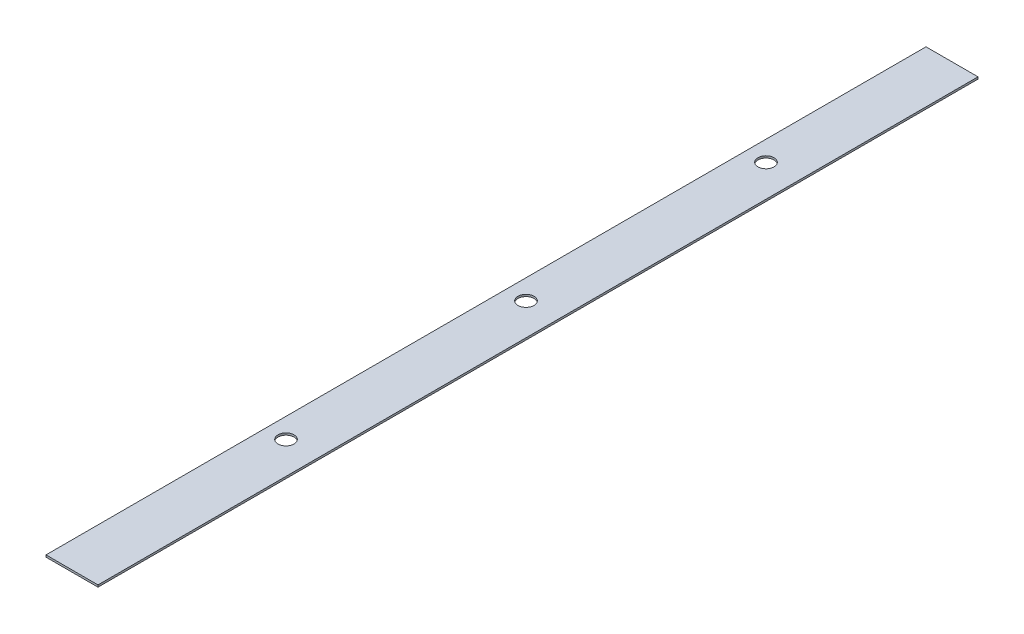
SolidWorks part; units mm, degrees
ref_plane "Plan de face" through (0, 0, 0) normal (0, 0, 1) x (1, 0, 0)
ref_plane "Plan de dessus" through (0, 0, 0) normal (0, 1, 0) x (1, 0, 0)
ref_plane "Plan de droite" through (0, 0, 0) normal (1, 0, 0) x (0, 0, -1)
sketch "Esquisse1" plane through (0, 0, 0) normal (0, 0, 1) x (1, 0, 0)
  line L0 (0, 0) -> (13, 0)
  line L1 (13, 0.5) -> (13, 0)
  line L2 (13, 0.5) -> (0, 0.5)
  line L3 (0, 0.5) -> (0, 0)
  dimension "D1" = 13
  dimension "D2" = 0.5
extrude "Boss.-Extru.1" add sketch "Esquisse1" along normal blind 220
sketch "Esquisse2" plane through (0, 0.5, 0) normal (0, 1, 0) x (1, 0, 0)
  circle A0 centre (5, -45) radius 2
  circle A1 centre (5, -105) radius 2
  circle A2 centre (5, -165) radius 2
  circle A4 centre (5, -225) radius 2 [skipped]
  dimension "D1" = 4
  dimension "D2" = 5
  dimension "D3" = 45
  dimension "D4" = 4
extrude "Enlèv. mat.-Extru.1" cut sketch "Esquisse2" against normal up to next
